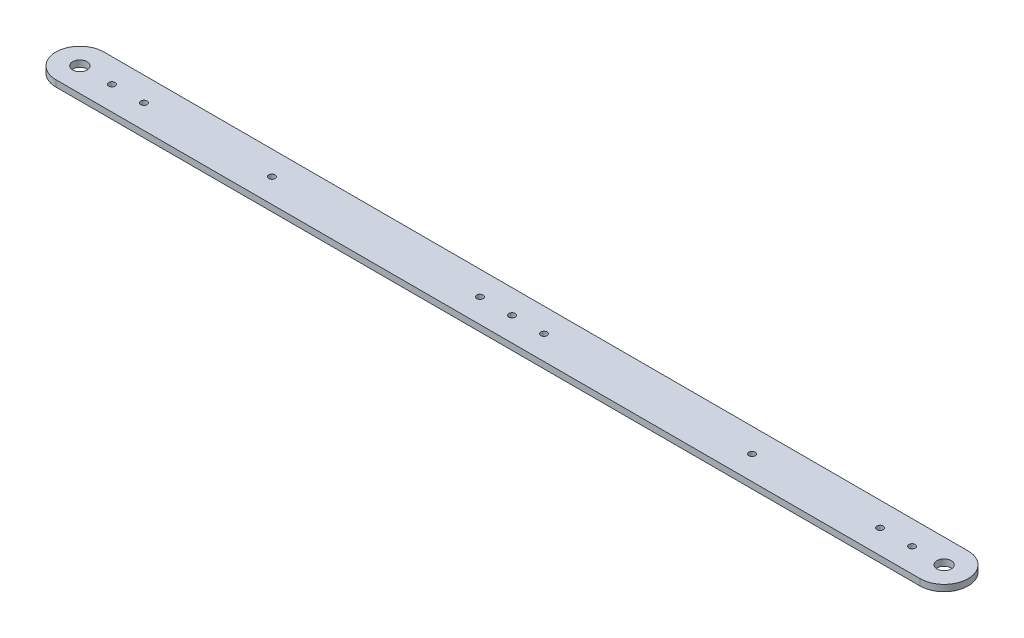
SolidWorks part; units mm, degrees
ref_plane "Front Plane" through (0, 0, 0) normal (0, 0, 1) x (1, 0, 0)
ref_plane "Top Plane" through (0, 0, 0) normal (0, 1, 0) x (1, 0, 0)
ref_plane "Right Plane" through (0, 0, 0) normal (1, 0, 0) x (0, 0, -1)
sketch "Sketch1" plane through (0, 0, 0) normal (0, 1, 0) x (1, 0, 0)
  line L0 (0, 0) -> (-270, 0) construction
  line L1 (0, 0) -> (270, 0) construction
  line L2 (-270, 15) -> (270, 15)
  line L3 (270, -15) -> (-270, -15)
  line L4 (0, 0) -> (0, 74.2689) construction
  circle A0 centre (-270, 0) radius 4.5
  circle A1 centre (270, 0) radius 4.5
  arc A2 (270, 15) -> (270, -15) centre (270, 0) cw
  arc A3 (-270, -15) -> (-270, 15) centre (-270, 0) cw
  circle A4 centre (-150, 0) radius 2
  circle A5 centre (150, 0) radius 2
  circle A6 centre (0, 0) radius 2
  circle A7 centre (-250, 0) radius 2
  circle A8 centre (-230, 0) radius 2
  circle A9 centre (-20, 0) radius 2
  circle A10 centre (230, 0) radius 2
  circle A11 centre (250, 0) radius 2
  circle A12 centre (20, 0) radius 2
  dimension "D3" = 9
  dimension "D4" = 15
  dimension "D5" = 4
  dimension "D6" = 150
  dimension "D7" = 20
  dimension "D1" = 270
  dimension "D2" = 270
  dimension "D8" = 20
  dimension "D9" = 20
  dimension "D10" = 150
extrude "Boss-Extrude1" add sketch "Sketch1" along normal blind 4
